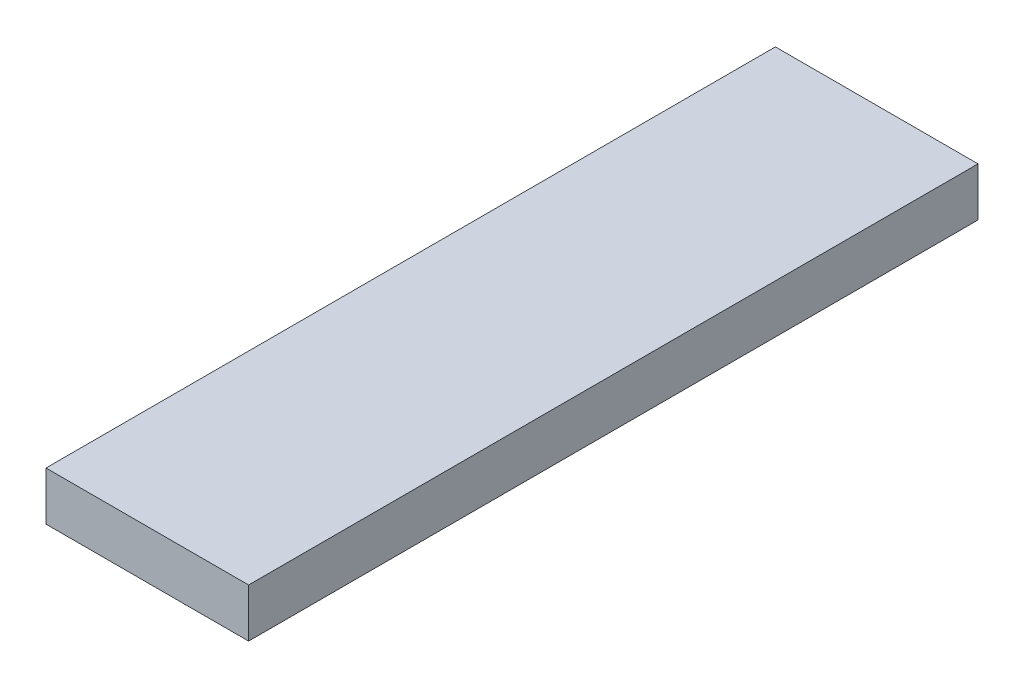
SolidWorks part; units mm, degrees
ref_plane "Plano frontal" through (0, 0, 0) normal (0, 0, 1) x (1, 0, 0)
ref_plane "Plano superior" through (0, 0, 0) normal (0, 1, 0) x (1, 0, 0)
ref_plane "Plano direito" through (0, 0, 0) normal (1, 0, 0) x (0, 0, -1)
sketch "Esboço1" plane through (0, 0, 0) normal (0, 1, 0) x (1, 0, 0)
  line L1 (-12.5, 45) -> (12.5, 45)
  line L2 (-12.5, 45) -> (-12.5, -45)
  line L3 (-12.5, -45) -> (12.5, -45)
  line L4 (12.5, 45) -> (12.5, -45)
  line L5 (-12.5, 45) -> (12.5, -45) construction
  line L6 (-12.5, -45) -> (12.5, 45) construction
  point P0 (0, 0)
extrude "Ressalto-extrusão1" add sketch "Esboço1" along normal blind 6
